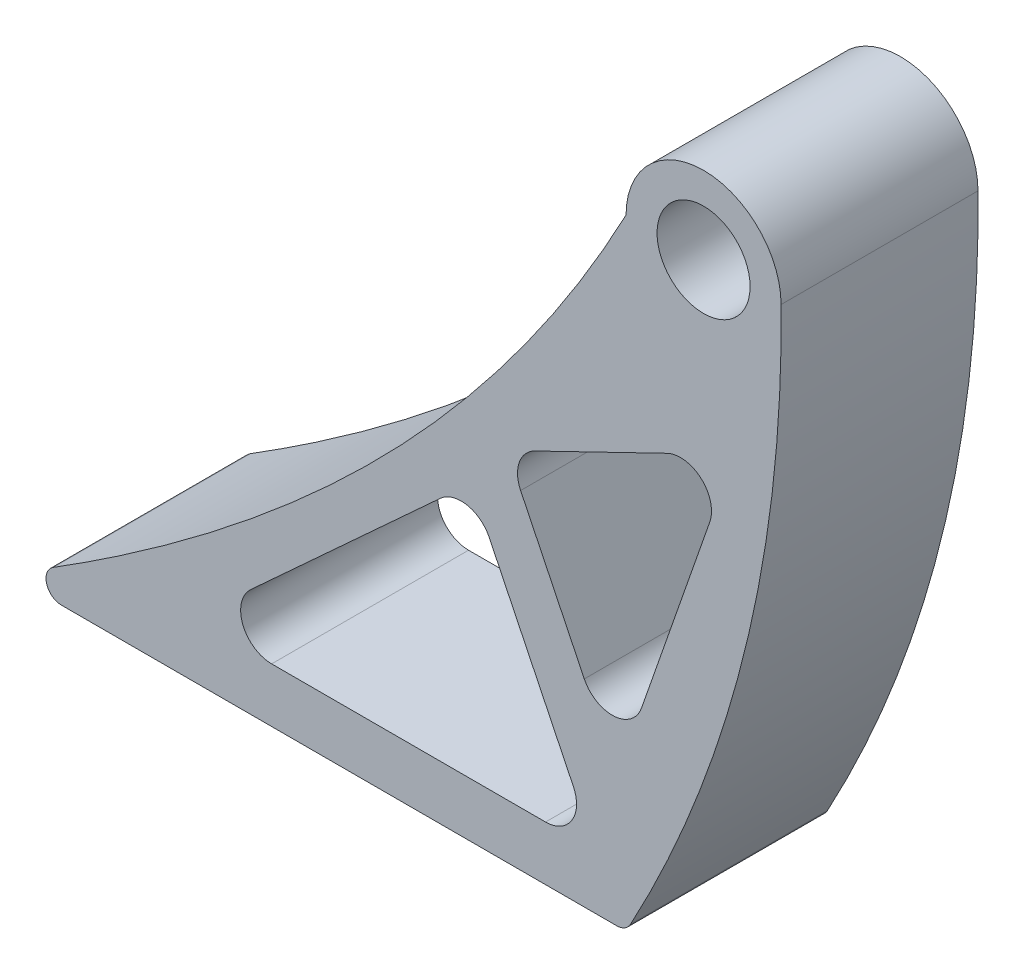
SolidWorks part; units mm, degrees
ref_plane "Front Plane" through (0, 0, 0) normal (0, 0, 1) x (1, 0, 0)
ref_plane "Top Plane" through (0, 0, 0) normal (0, 1, 0) x (1, 0, 0)
ref_plane "Right Plane" through (0, 0, 0) normal (1, 0, 0) x (0, 0, -1)
sketch "Croquis2" plane through (0, 0, 0) normal (0, 0, 1) x (1, 0, 0)
  line L0 (3.5877, 0) -> (39.4062, 0)
  line L1 (15.7902, 6.9743) -> (28.0205, 18.1854)
  line L2 (31.1716, 17.5837) -> (36.6072, 6.3725)
  line L3 (34.8076, 3.5) -> (17.1416, 3.5)
  line L4 (37.3071, 12.7424) -> (33.2004, 21.2124)
  line L5 (34.1274, 23.8846) -> (42.6399, 28.0118)
  line L6 (45.4003, 25.552) -> (40.9946, 12.9546)
  arc A0 (50, 40) -> (40, 40) centre (45, 40) ccw
  arc A1 (3.5877, 0) -> (3.0578, 1.8481) centre (3.5877, 1) cw
  circle A2 centre (45, 40) radius 3
  arc A3 (39.4062, 0) -> (40.2859, 0.5245) centre (39.4062, 1) ccw
  arc A4 (42.6399, 28.0118) -> (45.4003, 25.552) centre (43.5125, 26.2122) cw
  arc A5 (40.9946, 12.9546) -> (37.3071, 12.7424) centre (39.1067, 13.6149) cw
  arc A6 (33.2004, 21.2124) -> (34.1274, 23.8846) centre (35, 22.085) cw
  arc A7 (28.0205, 18.1854) -> (31.1716, 17.5837) centre (29.3719, 16.7111) cw
  arc A8 (36.6072, 6.3725) -> (34.8076, 3.5) centre (34.8076, 5.5) cw
  arc A9 (15.7902, 6.9743) -> (17.1416, 3.5) centre (17.1416, 5.5) ccw
  spline S0 degree 3 poles (3.0578, 1.8481) (18.6585, 11.596) (31.5005, 23.9377) (40, 40) knots 0.060557 0.060557 0.060557 0.060557 1 1 1 1
  spline S1 degree 3 poles (40.2859, 0.5245) (46.911, 12.7814) (50.153, 25.954) (50, 40) knots 0.014078 0.014078 0.014078 0.014078 1 1 1 1
  dimension "D1" = 1
  dimension "D2" = 1
  dimension "D3" = 2
extrude "Saliente-Extruir1" add sketch "Croquis2" along normal blind 12.7
